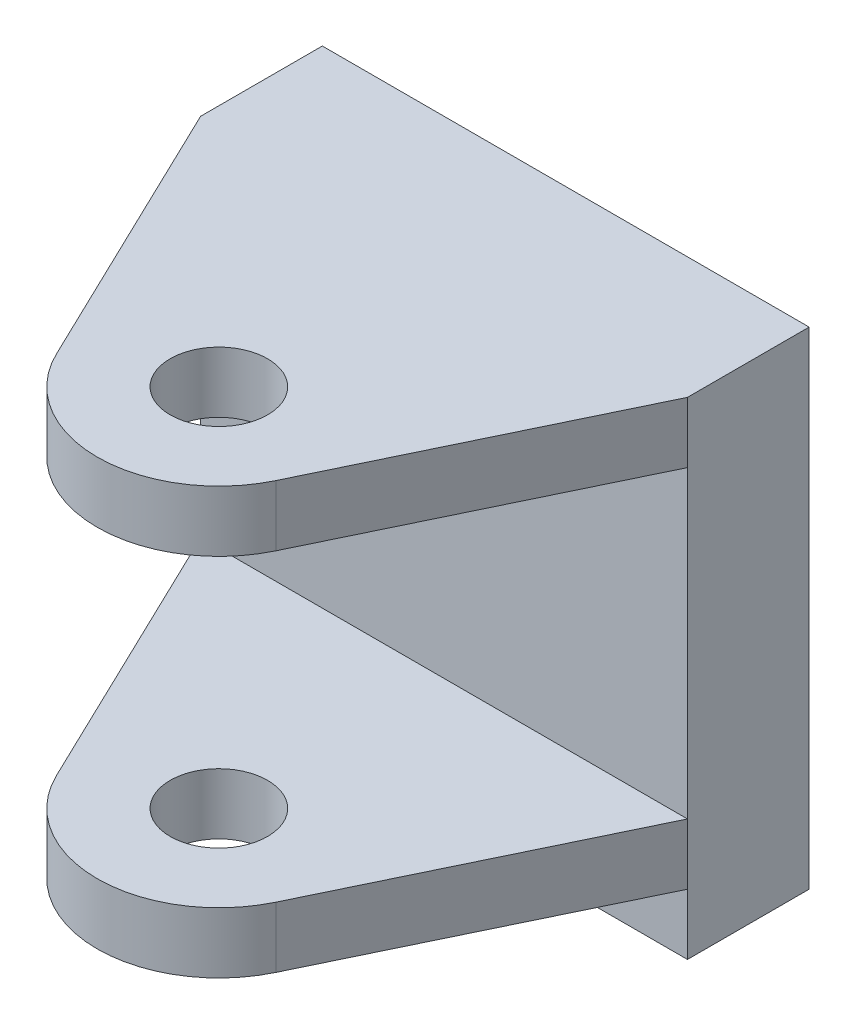
SolidWorks part; units mm, degrees
ref_plane "前视基准面" through (0, 0, 0) normal (0, 0, 1) x (1, 0, 0)
ref_plane "上视基准面" through (0, 0, 0) normal (0, 1, 0) x (1, 0, 0)
ref_plane "右视基准面" through (0, 0, 0) normal (1, 0, 0) x (0, 0, -1)
sketch "草图1" plane through (0, 0, 0) normal (0, 0, 1) x (1, 0, 0)
  line L1 (-20, 20) -> (20, 20)
  line L2 (-20, 20) -> (-20, -20)
  line L3 (-20, -20) -> (20, -20)
  line L4 (20, 20) -> (20, -20)
  line L5 (-20, 20) -> (20, -20) construction
  line L6 (-20, -20) -> (20, 20) construction
  point P0 (0, 0)
  dimension "D1" = 40
  dimension "D2" = 40
extrude "凸台-拉伸1" add sketch "草图1" along normal blind 10
ref_plane "基准面1" through (0, 15, 0) normal (0, 1, 0) x (1, 0, 0)
sketch "草图2" plane through (0, 15, 0) normal (0, 1, 0) x (1, 0, 0)
  line L0 (-20, -10) -> (-9.011, -32.8362)
  line L1 (20, -10) -> (9.011, -32.8362)
  line L2 (-20, -10) -> (20, -10)
  circle A0 centre (0, -28.5) radius 4
  circle A1 centre (0, -28.5) radius 10
  dimension "D2" = 8
  dimension "D3" = 20
  dimension "D1" = 28.5
extrude "凸台-拉伸2" add sketch "草图2" along normal blind 5 contours A1 L1 L2 L0 | A1 A0
pattern_linear "阵列(线性)1" count 2 spacing 30 along (0, -1, 0) of "凸台-拉伸2"
